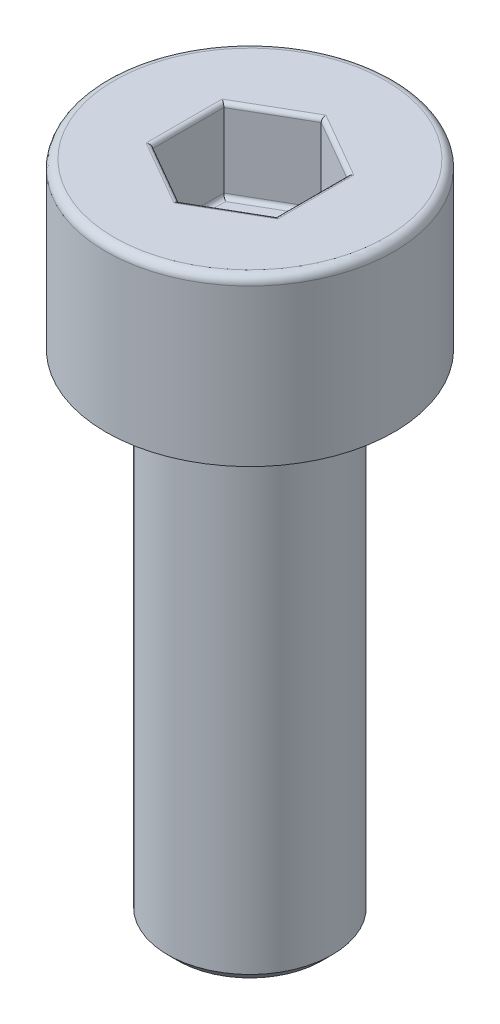
SolidWorks part; units mm, degrees
ref_plane "Front Plane" through (0, 0, 0) normal (0, 0, 1) x (1, 0, 0)
ref_plane "Top Plane" through (0, 0, 0) normal (0, 1, 0) x (1, 0, 0)
ref_plane "Right Plane" through (0, 0, 0) normal (1, 0, 0) x (0, 0, -1)
sketch "Sketch1" plane through (0, 0, 0) normal (0, 0, 1) x (1, 0, 0)
  line L0 (0, 0) -> (0, -47.0967) construction
  line L1 (0, -16) -> (-2, -16)
  line L2 (-2, -16) -> (-2, -4)
  line L3 (-2, -4) -> (-3.5, -4)
  line L4 (-3.5, -4) -> (-3.5, 0)
  line L5 (-3.5, 0) -> (0, 0)
  line L6 (0, 0) -> (0, -16)
  dimension "d" = 4
  dimension "l" = 16
  dimension "k" = 4
  dimension "dk" = 7
revolve "Revolve1" add sketch "Sketch1" angle 360 about L0
chamfer "Chamfer1" distance 0.25 angle 45 2 edges at (0, -4, 2) (0, -16, 2)
fillet "Fillet1" radius 0.2 1 edges at (0, 0, 3.5)
sketch "Sketch2" plane through (0, 0, 0) normal (0, 1, 0) x (1, 0, 0)
  line L1 (0, 1.7321) -> (-1.5, 0.866)
  line L2 (-1.5, 0.866) -> (-1.5, -0.866)
  line L3 (-1.5, -0.866) -> (0, -1.7321)
  line L4 (0, -1.7321) -> (1.5, -0.866)
  line L5 (1.5, -0.866) -> (1.5, 0.866)
  line L6 (1.5, 0.866) -> (0, 1.7321)
  circle A0 centre (0, 0) radius 1.5 construction
  dimension "s" = 3
extrude "Cut-Extrude1" cut sketch "Sketch2" against normal blind 2
fillet "Fillet2" radius 0.1 12 edges at (-0.75, 0, -1.299) (-1.5, 0, 0) (-0.75, 0, 1.299) (0.75, 0, 1.299) (1.5, 0, 0) (0.75, 0, -1.299) (1.5, -2, 0) (0.75, -2, 1.299) (-0.75, -2, 1.299) (-1.5, -2, 0) (-0.75, -2, -1.299) (0.75, -2, -1.299)
